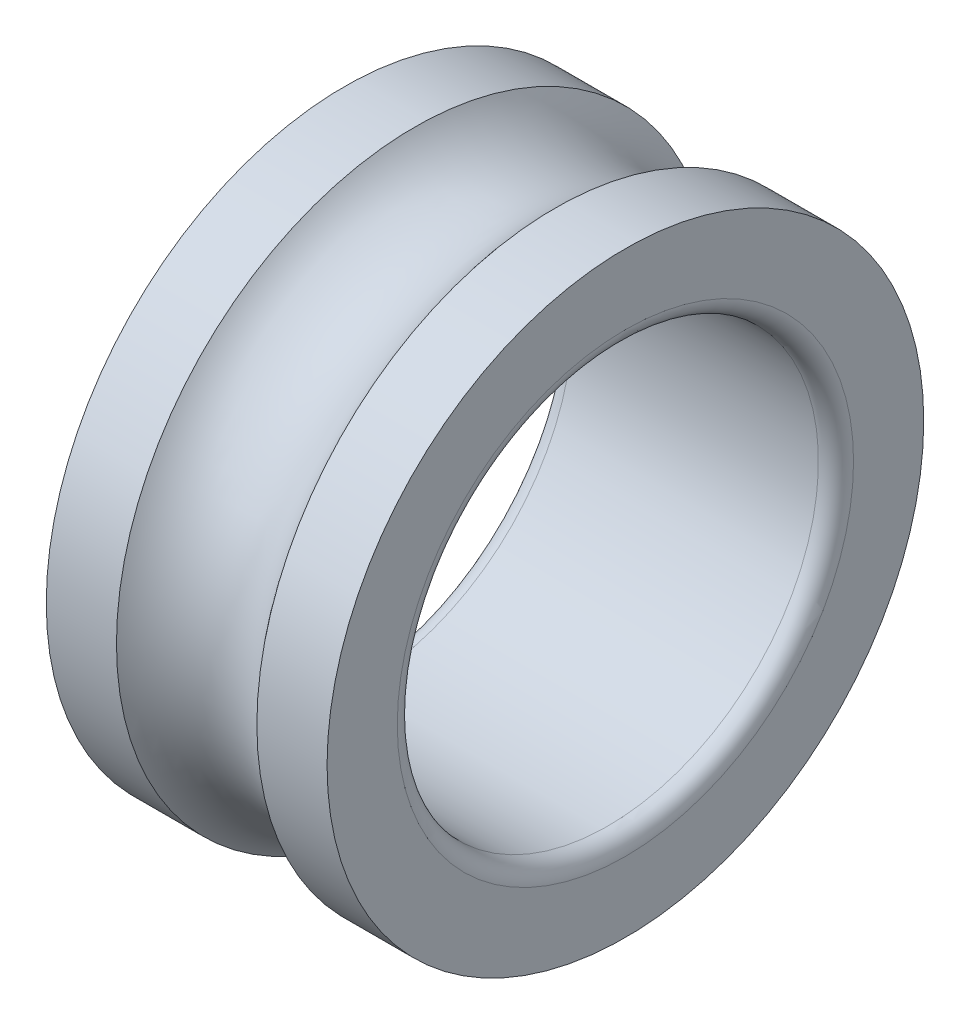
SolidWorks part; units mm, degrees
ref_plane "Plan1" through (0, 0, 0) normal (0, 0, 1) x (1, 0, 0)
ref_plane "Plan2" through (0, 0, 0) normal (0, 1, 0) x (1, 0, 0)
ref_plane "Plan3" through (0, 0, 0) normal (1, 0, 0) x (0, 0, -1)
sketch "Esquisse1" plane through (0, 0, 0) normal (0, 0, 1) x (1, 0, 0)
  line L0 (6, 8.5) -> (8, 8.5)
  line L1 (0, 8.5) -> (0, 6.5)
  line L2 (7.5, 6) -> (0.5, 6)
  line L3 (8, 6.5) -> (8, 8.5)
  line L4 (0, 8.5) -> (2, 8.5)
  line L5 (0, 0) -> (9, 0) construction
  arc A0 (2, 8.5) -> (6, 8.5) centre (4, 10) ccw
  arc A1 (0.5, 6) -> (0, 6.5) centre (0.5, 6.5) cw
  arc A2 (8, 6.5) -> (7.5, 6) centre (7.5, 6.5) cw
  point P10 (0, 6)
  dimension "D3" = 5
  dimension "D2" = 0.5
  dimension "D1" = 6
  dimension "D4" = 10
  dimension "D5" = 4
  dimension "D6" = 2.5
revolve "Base-Révolution" add sketch "Esquisse1" angle 360 about L5
